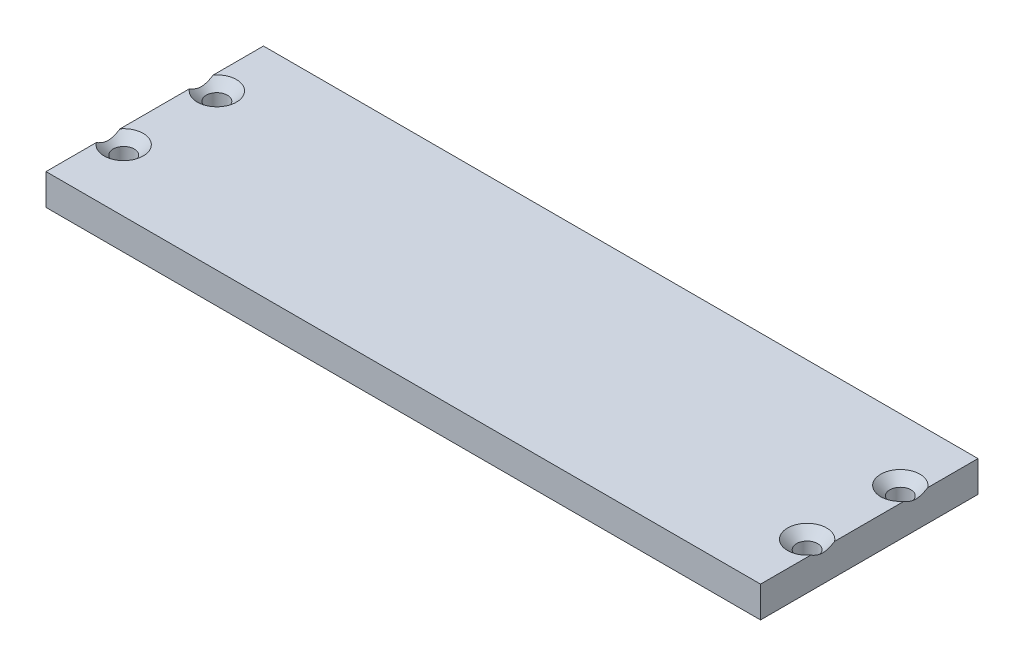
SolidWorks part; units mm, degrees
material "Acrylic"
ref_plane "Front" through (0, 0, 0) normal (0, 0, 1) x (1, 0, 0)
ref_plane "Top" through (0, 0, 0) normal (0, 1, 0) x (1, 0, 0)
ref_plane "Right" through (0, 0, 0) normal (1, 0, 0) x (0, 0, -1)
sketch "Sketch1" plane through (0, 0, 0) normal (0, 1, 0) x (1, 0, 0)
  line L1 (0, 0) -> (115, 0)
  line L2 (0, 0) -> (0, 35)
  line L3 (0, 35) -> (115, 35)
  line L4 (115, 0) -> (115, 35)
  dimension "D1" = 35
  dimension "D2" = 115
extrude "Boss-Extrude1" add sketch "Sketch1" against normal blind 5
hole_wizard "CSK for M3 Flat Countersunk Head Screw1" positions "Sketch2" profile "Sketch3" countersink size "M3" standard "JIS" end condition through all
sketch "Sketch2" plane through (0, 0, 0) normal (0, 1, 0) x (1, 0, 0)
  line L0 (0, 35) -> (0, 0) construction
  line L1 (0, 0) -> (115, 0) construction
  point P0 (2.5, 25)
  point P2 (2.5, 10)
  point P4 (112.5, 25)
  point P6 (112.5, 10)
  dimension "D1" = 2.5
  dimension "D2" = 112.5
  dimension "D3" = 25
  dimension "D4" = 10
sketch "Sketch3" plane through (2.5, 0, -25) normal (1, 0, 0) x (0, 0, 1)
  line L0 (0, 0) -> (0, 5)
  line L1 (0, 5) -> (1.7, 5)
  line L2 (1.7, 5) -> (1.7, 1.45)
  line L3 (1.7, 1.45) -> (3.15, 0)
  line L5 (3.15, 0) -> (0, 0)
  line L6 (-1.7, 1.45) -> (-3.15, 0) construction
  line L11 (0, -6.35) -> (0, 107.95) construction
  dimension "Thru Hole Dia." = 3.4
  dimension "Thru Hole Depth" = 5
  dimension "Near C'Sink Dia." = 6.3
  dimension "Near C'Sink Angle" = 90
